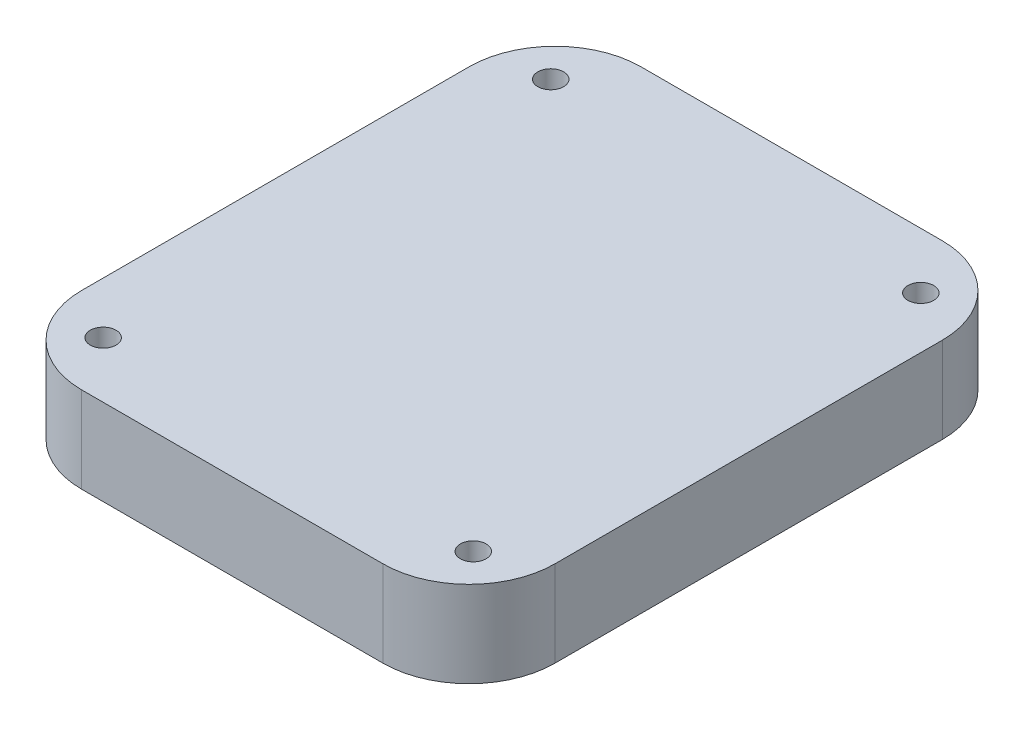
SolidWorks part; units mm, degrees
ref_plane "Front Plane" through (0, 0, 0) normal (0, 0, 1) x (1, 0, 0)
ref_plane "Top Plane" through (0, 0, 0) normal (0, 1, 0) x (1, 0, 0)
ref_plane "Right Plane" through (0, 0, 0) normal (1, 0, 0) x (0, 0, -1)
sketch "Sketch1" plane through (0, 0, 0) normal (0, 1, 0) x (1, 0, 0)
  line L1 (-17.5, 32.5) -> (17.5, 32.5)
  line L2 (-27.5, 22.5) -> (-27.5, -22.5)
  line L3 (-17.5, -32.5) -> (17.5, -32.5)
  line L4 (27.5, 22.5) -> (27.5, -22.5)
  arc A0 (-27.5, -22.5) -> (-17.5, -32.5) centre (-17.5, -22.5) ccw
  arc A1 (17.5, -32.5) -> (27.5, -22.5) centre (17.5, -22.5) ccw
  arc A2 (17.5, 32.5) -> (27.5, 22.5) centre (17.5, 22.5) cw
  arc A3 (-17.5, 32.5) -> (-27.5, 22.5) centre (-17.5, 22.5) ccw
  point P9 (-27.5, -32.5)
  point P14 (27.5, 32.5)
  point P17 (-27.5, 32.5)
  dimension "D3" = 10
  dimension "D1" = 55
  dimension "D2" = 65
extrude "Boss-Extrude1" add sketch "Sketch1" along normal blind 10 contours L1 A2 L4 A1 L3 A0 L2 A3
sketch "Sketch3" plane through (0, 10, 0) normal (0, 1, 0) x (1, 0, 0)
  line L0 (-21.5, 26) -> (-21.5, -26) construction
  line L1 (-21.5, -26) -> (21.5, -26) construction
  line L2 (21.5, -26) -> (21.5, 26) construction
  line L3 (21.5, 26) -> (-21.5, 26) construction
  circle A0 centre (-21.5, 26) radius 1.5
  circle A1 centre (21.5, 26) radius 1.5
  circle A2 centre (21.5, -26) radius 1.5
  circle A3 centre (-21.5, -26) radius 1.5
  point P2 (0, 26)
  point P5 (-21.5, 0)
  dimension "D3" = 3
  dimension "D1" = 43
  dimension "D2" = 52
  dimension "D4" = 2
  dimension "D5" = 2
extrude "Cut-Extrude3" cut sketch "Sketch3" against normal through all
